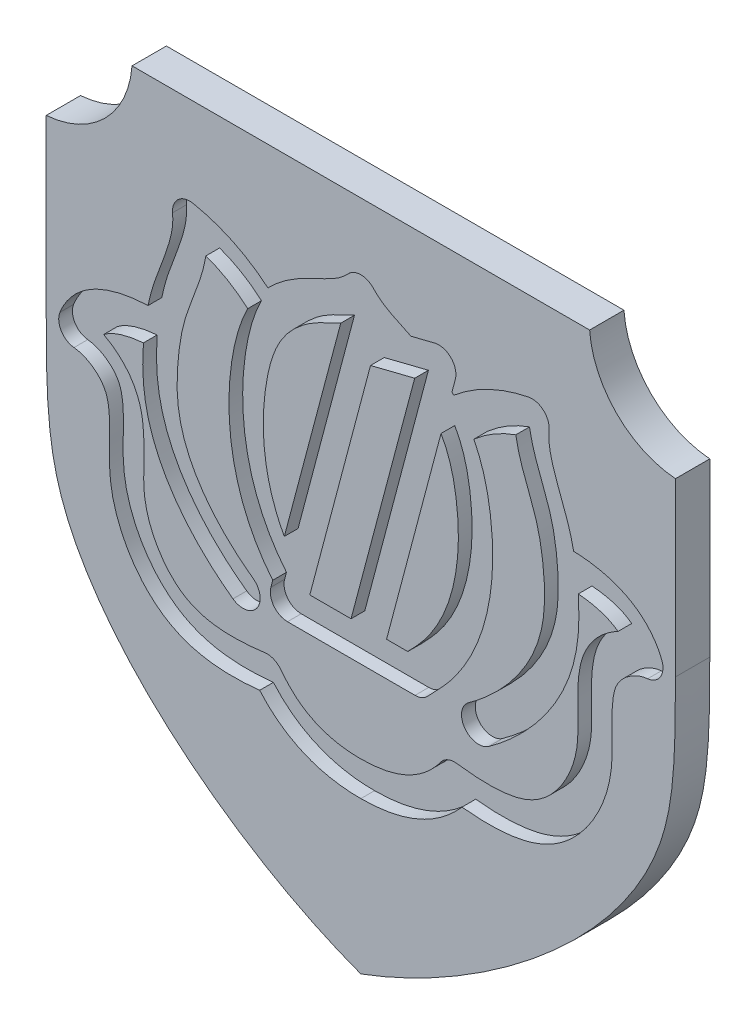
SolidWorks part; units mm, degrees
ref_plane "前视基准面" through (0, 0, 0) normal (0, 0, 1) x (1, 0, 0)
ref_plane "上视基准面" through (0, 0, 0) normal (0, 1, 0) x (1, 0, 0)
ref_plane "右视基准面" through (0, 0, 0) normal (1, 0, 0) x (0, 0, -1)
sketch "草图2" plane through (0, 0, 0) normal (0, 0, 1) x (1, 0, 0)
  line L0 (4.1494, 56.5411) -> (40.8033, 56.5411)
  line L1 (40.8033, 56.5411) -> (40.8033, 44.5411)
  line L2 (22.4764, 6.2707) -> (22.4764, 51.3385) construction
  line L3 (39.8279, 35.4814) -> (22.4764, 35.4814) construction
  line L4 (32.8077, 26.4279) -> (22.4764, 26.4279) construction
  line L5 (40.8033, 44.5411) -> (22.4764, 44.5411) construction
  line L6 (4.1494, 56.5411) -> (4.1494, 44.5411)
  spline S0 degree 3 poles (40.8033, 44.5411) (40.8033, 40.3535) (40.4908, 31.4372) (29.5833, 23.023) (22.4764, 20.3922) knots 0 0 0 0 0.275347 1 1 1 1
  spline S1 degree 3 poles (4.1494, 44.5411) (4.1494, 40.3535) (4.462, 31.4372) (15.3695, 23.023) (22.4764, 20.3922) knots 0 0 0 0 0.275347 1 1 1 1
  point P12 (39.4584, 36.4939)
  point P14 (35.0581, 29.6079)
  point P18 (28.0508, 24.7227)
  point P20 (22.4764, 23.2071)
  point P21 (29.4506, 25.5175)
  point P39 (22.4764, 56.5411)
  dimension "D1" = 32.7641
  dimension "D2" = 18.3269
  dimension "D3" = 17.3516
  dimension "D4" = 10.3313
  dimension "D5" = 6.0357
  dimension "D7" = 9.0535
  dimension "D8" = 9.0597
  dimension "D9" = 12
extrude "凸台-拉伸1" add sketch "草图2" along normal blind 2 contours L1 S0 S1 L6 L0
sketch "草图3" plane through (0, 0, 0) normal (0, 0, -1) x (-1, 0, 0)
  line L0 (39, 165) -> (195, 165) construction
sketch "草图4" plane through (0, 0, 2) normal (0, 0, 1) x (1, 0, 0)
  line L0 (22.4764, 56.5411) -> (22.4764, 20.3922) construction
  line L1 (4.1494, 56.5411) -> (40.8033, 56.5411) construction
  line L2 (18.2036, 37.0255) -> (22.2235, 52.1947) construction
  line L3 (22.2235, 52.1947) -> (27.0152, 53.3994) construction
  line L4 (27.0152, 53.3994) -> (22.676, 37.0255) construction
  line L5 (22.676, 37.0255) -> (18.2036, 37.0255) construction
  line L6 (22.676, 37.0255) -> (25.6338, 37.0255) construction
  line L20 (23.4455, 36.0255) -> (18.2036, 36.0255)
  line L21 (17.2369, 37.2816) -> (17.3448, 37.6886)
  line L23 (27.9818, 53.1433) -> (27.7842, 52.3973)
  line L24 (23.9755, 38.0255) -> (25.2114, 38.0255)
  line L25 (21.9065, 38.0255) -> (19.5031, 38.0255)
  line L26 (19.5031, 38.0255) -> (23.0391, 51.3686)
  line L27 (23.0391, 51.3686) -> (25.6141, 52.016)
  line L28 (25.6141, 52.016) -> (21.9065, 38.0255)
  line L29 (22.676, 36.0255) -> (25.6336, 36.0255)
  line L30 (25.3951, 54.0232) -> (26.7714, 54.3693)
  line L31 (27.1473, 49.9942) -> (23.9755, 38.0255)
  line L32 (18.0197, 40.2355) -> (21.3066, 52.6386)
  line L33 (16.6154, 35.7475) -> (15.6117, 36.4052) construction
  line L34 (16.1946, 37.2177) -> (15.0288, 35.5926) construction
  line L35 (28.7582, 37.2177) -> (29.924, 35.5926) construction
  line L36 (28.7582, 37.2177) -> (29.924, 35.5926) construction
  line L37 (28.3373, 35.7475) -> (29.341, 36.4052) construction
  arc A21 (26.3397, 36.3174) -> (25.6336, 36.0255) centre (25.6336, 37.0255) cw
  arc A22 (18.2036, 36.0255) -> (17.2369, 37.2816) centre (18.2036, 37.0255) cw
  arc A23 (23.2115, 55.3452) -> (21.7426, 55.3475) centre (22.476, 54.6677) ccw
  arc A24 (26.7714, 54.3693) -> (27.9818, 53.1433) centre (27.0152, 53.3994) cw
  arc A25 (32.2425, 54.3779) -> (33.4427, 53.308) centre (32.4468, 53.399) cw
  arc A26 (39.1836, 43.6386) -> (40.002, 45.0103) centre (39.076, 44.6328) ccw
  arc A27 (27.1371, 33.4134) -> (28.064, 33.8057) centre (27.9374, 32.8137) cw
  arc A28 (16.8888, 33.8057) -> (17.8156, 33.4134) centre (17.0154, 32.8137) cw
  arc A29 (12.7102, 54.3779) -> (11.5101, 53.308) centre (12.5059, 53.399) ccw
  arc A30 (4.9508, 45.0103) -> (5.7691, 43.6386) centre (5.8768, 44.6328) ccw
  arc A33 (16.1946, 37.2177) -> (15.0288, 35.5926) centre (15.6117, 36.4052) cw
  arc A34 (28.7582, 37.2177) -> (29.924, 35.5926) centre (29.3411, 36.4052) ccw
  spline S0 degree 3 poles (22.4764, 54.6675) (21.5957, 53.6967) (19.4078, 53.1306) (16.7241, 50.7619) (15.5245, 46.4292) (15.8922, 41.6848) (17.6479, 38.8117) (18.4474, 37.9456) knots 0 0 0 0 0.184464 0.328772 0.505894 0.829967 1 1 1 1 construction
  spline S1 degree 3 poles (22.4764, 54.6675) (23.2535, 53.8109) (24.3007, 53.4628) (25.2837, 52.9641) knots 0 0 0 0 0.16277 0.16277 0.16277 0.16277 construction
  spline S2 degree 2 poles (26.5054, 37.9456) (25.9014, 37.2913) (25.6338, 37.0255) knots 0 0 0 1 1 1 construction
  spline S3 degree 3 poles (26.6622, 52.0676) (27.1111, 51.6935) (28.3381, 50.3666) (29.4283, 46.4292) (29.0605, 41.6848) (27.3048, 38.8117) (26.5054, 37.9456) knots 0.243353 0.243353 0.243353 0.243353 0.328772 0.505894 0.829967 1 1 1 1 construction
  spline S4 degree 2 poles (17.157, 50.8362) (15.2274, 52.8532) (12.506, 53.3994) knots 0 0 0 1 1 1 construction
  spline S5 degree 3 poles (12.506, 53.3994) (12.6565, 51.9187) (11.4669, 49.5818) (10.8419, 46.8735) (10.457, 40.4605) (14.5182, 36.9921) (16.6154, 35.7475) knots 0 0 0 0 0.222641 0.34958 0.494422 1 1 1 1 construction
  spline S6 degree 3 poles (10.9236, 46.9057) (9.0932, 47) (6.6678, 46.6159) (5.8768, 44.6327) knots 0 0 0 0 1 1 1 1 construction
  spline S7 degree 3 poles (5.8768, 44.6327) (6.9592, 44.5209) (8.5039, 43.4661) (8.9816, 40.7155) (8.4519, 37.2808) (11.3933, 32.42) (15.3797, 32.6) (17.0154, 32.8139) knots 0 0 0 0 0.17617 0.249065 0.433904 0.728589 1 1 1 1 construction
  spline S8 degree 2 poles (17.0154, 32.8139) (18.934, 30.239) (22.4764, 30.239) knots 0 0 0 1 1 1 construction
  spline S9 degree 2 poles (27.9374, 32.8139) (26.0188, 30.239) (22.4764, 30.239) knots 0 0 0 1 1 1 construction
  spline S10 degree 3 poles (39.076, 44.6327) (37.9935, 44.5209) (36.4489, 43.4661) (35.9712, 40.7155) (36.5009, 37.2808) (33.5594, 32.42) (29.5731, 32.6) (27.9374, 32.8139) knots 0 0 0 0 0.17617 0.249065 0.433904 0.728589 1 1 1 1 construction
  spline S11 degree 3 poles (34.0292, 46.9057) (35.8596, 47) (38.285, 46.6159) (39.076, 44.6327) knots 0 0 0 0 1 1 1 1 construction
  spline S12 degree 3 poles (32.4468, 53.3994) (32.2963, 51.9187) (33.4859, 49.5818) (34.1109, 46.8735) (34.4958, 40.4605) (30.4346, 36.9921) (28.3373, 35.7475) knots 0 0 0 0 0.222641 0.34958 0.494422 1 1 1 1 construction
  spline S13 degree 2 poles (27.7958, 50.8362) (29.7253, 52.8532) (32.4468, 53.3994) knots 0 0 0 1 1 1 construction
  spline S14 degree 3 poles (9.8113, 45.8961) (9.5472, 45.8759) (8.9669, 45.8016) (8.146, 45.561) (7.704, 45.3196) (7.4963, 45.162) knots 0.206327 0.206327 0.206327 0.206327 0.358363 0.537545 0.716726 0.716726 0.716726 0.716726
  spline S15 degree 3 poles (21.3066, 52.6386) (21.2982, 52.6345) (20.9026, 52.4399) (20.1528, 52.1116) (19.2561, 51.5915) (18.4482, 50.895) (17.8305, 50.1052) (17.2406, 48.8823) (16.8387, 47.0036) (16.7375, 44.6753) (17.0676, 42.4325) (17.6065, 40.9968) (17.9869, 40.2945) (18.0197, 40.2355) knots 0.097335 0.097335 0.097335 0.097335 0.098633 0.158724 0.218815 0.278906 0.338997 0.399088 0.519271 0.639453 0.759635 0.879818 0.890912 0.890912 0.890912 0.890912
  spline S16 degree 2 poles (17.0649, 52.2933) (16.4131, 52.8417) (15.085, 53.611) (14.0068, 54.0395) (13.219, 54.2696) (12.7888, 54.3616) (12.7102, 54.3779) knots 0.183706 0.183706 0.183706 0.466542 0.699814 0.855328 0.971963 0.999219 0.999219 0.999219
  spline S17 degree 3 poles (11.5101, 53.308) (11.5186, 53.2145) (11.5283, 53.0696) (11.5208, 52.7247) (11.4383, 52.1045) (11.1453, 51.1255) (10.648, 49.8889) (10.2828, 48.8082) (10.1286, 48.1504) (10.0805, 47.9132) knots -0.000426 -0.000426 -0.000426 -0.000426 0.015831 0.032512 0.065874 0.132597 0.19932 0.266044 0.302183 0.302183 0.302183 0.302183
  spline S18 degree 2 poles (27.8873, 52.2928) (28.5393, 52.8415) (29.8678, 53.611) (30.946, 54.0395) (31.7338, 54.2696) (32.164, 54.3616) (32.2425, 54.3779) knots 0.183578 0.183578 0.183578 0.466542 0.699814 0.855328 0.971963 0.999219 0.999219 0.999219
  spline S19 degree 3 poles (35.1415, 45.8961) (35.1439, 45.8624) (35.1826, 45.2963) (35.2067, 44.125) (34.9587, 42.4085) (34.2455, 40.3437) (33.1184, 38.5891) (31.8089, 37.1551) (30.8339, 36.277) (30.2083, 35.7966) (29.924, 35.5926) knots 0.395261 0.395261 0.395261 0.395261 0.39949 0.466213 0.532937 0.59966 0.733107 0.79983 0.866553 0.92413 0.92413 0.92413 0.92413
  spline S20 degree 3 poles (9.8113, 45.8961) (9.8089, 45.8624) (9.7701, 45.2963) (9.746, 44.125) (9.9941, 42.4085) (10.7073, 40.3437) (11.8343, 38.5891) (13.1439, 37.1551) (14.1188, 36.277) (14.7445, 35.7966) (15.0288, 35.5926) knots 0.395261 0.395261 0.395261 0.395261 0.39949 0.466213 0.532937 0.59966 0.733107 0.79983 0.866553 0.92413 0.92413 0.92413 0.92413
  spline S21 degree 3 poles (15.891, 50.6646) (15.4915, 49.8916) (14.959, 48.0881) (14.7027, 45.3428) (14.9796, 42.4266) (15.7623, 40.118) (16.6554, 38.5818) (17.1451, 37.9305) (17.3448, 37.6886) knots 0.362153 0.362153 0.362153 0.362153 0.474145 0.605609 0.737073 0.868536 0.934268 0.975477 0.975477 0.975477 0.975477
  spline S22 degree 3 poles (29.061, 50.664) (29.3118, 50.1765) (29.7617, 48.9767) (30.0989, 47.0765) (30.2424, 44.2832) (29.7702, 41.4989) (28.5892, 38.9584) (27.7244, 37.7919) (27.2402, 37.2673) knots 0.362177 0.362177 0.362177 0.362177 0.432515 0.527095 0.621676 0.810838 0.905419 1 1 1 1
  spline S24 degree 3 poles (10.0805, 47.9132) (10.0617, 47.9126) (9.719, 47.9) (9.0198, 47.8405) (7.9924, 47.6233) (6.9822, 47.2341) (6.0441, 46.6265) (5.3858, 45.8778) (5.076, 45.3109) (4.9683, 45.0532) (4.9508, 45.0103) knots 0.14203 0.14203 0.14203 0.14203 0.150826 0.301651 0.452477 0.603303 0.754129 0.904954 0.980367 0.99907 0.99907 0.99907 0.99907
  spline S25 degree 3 poles (5.7691, 43.6386) (5.7786, 43.6375) (5.829, 43.6319) (5.9212, 43.6185) (6.1675, 43.5652) (6.6428, 43.3843) (7.1523, 43.0168) (7.5016, 42.5627) (7.7212, 42.1114) (7.8531, 41.2853) (7.8472, 40.1402) (7.8041, 38.8806) (7.923, 37.4519) (8.3502, 36.0352) (9.027, 34.7129) (9.9441, 33.5402) (11.0941, 32.5823) (12.4678, 31.962) (13.8719, 31.6914) (15.2749, 31.6454) (16.1434, 31.7094) (16.5837, 31.7558) knots 0.000073 0.000073 0.000073 0.000073 0.001868 0.01001 0.026295 0.058865 0.124004 0.156574 0.189143 0.254282 0.319422 0.384561 0.4497 0.514839 0.579978 0.645118 0.710257 0.775396 0.840535 0.905674 0.970814 0.970814 0.970814 0.970814
  spline S26 degree 2 poles (16.5837, 31.7558) (17.3985, 30.8142) (19.154, 29.82) (21.1288, 29.2354) (22.4764, 29.239) knots 0.081569 0.081569 0.081569 0.425981 0.655589 1 1 1
  spline S27 degree 2 poles (22.4764, 29.239) (23.824, 29.2354) (25.7988, 29.82) (27.5542, 30.8142) (28.369, 31.7558) knots 0.081569 0.081569 0.081569 0.425981 0.655589 1 1 1
  spline S28 degree 3 poles (28.369, 31.7558) (28.8094, 31.7094) (29.6779, 31.6454) (31.0809, 31.6914) (32.485, 31.962) (33.8587, 32.5823) (35.0086, 33.5402) (35.9258, 34.7129) (36.6025, 36.0352) (37.0297, 37.4519) (37.1487, 38.8806) (37.1056, 40.1402) (37.0996, 41.2853) (37.2315, 42.1114) (37.4512, 42.5627) (37.8005, 43.0168) (38.31, 43.3843) (38.7853, 43.5652) (39.0316, 43.6185) (39.1238, 43.6319) (39.1741, 43.6375) (39.1836, 43.6386) knots -0.071414 -0.071414 -0.071414 -0.071414 -0.006275 0.058865 0.124004 0.189143 0.254282 0.319422 0.384561 0.4497 0.514839 0.579978 0.645118 0.710257 0.742826 0.775396 0.840535 0.873105 0.88939 0.897532 0.899327 0.899327 0.899327 0.899327
  spline S29 degree 3 poles (40.002, 45.0103) (39.9845, 45.0532) (39.8768, 45.3109) (39.567, 45.8778) (38.9087, 46.6265) (37.9706, 47.2341) (36.9604, 47.6233) (35.933, 47.8405) (35.2338, 47.9) (34.8911, 47.9126) (34.8722, 47.9132) knots 0.207536 0.207536 0.207536 0.207536 0.226239 0.301651 0.452477 0.603303 0.754129 0.904954 1.05578 1.064576 1.064576 1.064576 1.064576
  spline S32 degree 3 poles (25.3951, 54.0232) (25.3358, 54.0515) (25.1051, 54.1605) (24.5656, 54.4091) (23.995, 54.702) (23.5925, 54.9868) (23.3784, 55.1728) (23.285, 55.2658) (23.2202, 55.3357) (23.2115, 55.3452) knots -0.034078 -0.034078 -0.034078 -0.034078 -0.0249 0.00191 0.05553 0.08234 0.095745 0.10915 0.111193 0.111193 0.111193 0.111193
  spline S33 degree 3 poles (21.7426, 55.3475) (21.6849, 55.2852) (21.5224, 55.1163) (21.1928, 54.8577) (20.5595, 54.4806) (19.5846, 54.0559) (18.2255, 53.3372) (17.4285, 52.671) (17.066, 52.2944) (17.0649, 52.2933) knots -0.000191 -0.000191 -0.000191 -0.000191 0.014022 0.046888 0.079754 0.145486 0.211218 0.27695 0.277144 0.277144 0.277144 0.277144
  spline S36 degree 3 poles (27.1473, 49.9942) (27.3948, 49.5743) (27.7896, 48.5994) (28.1081, 46.8451) (28.2304, 44.4136) (27.8237, 42.059) (26.8549, 39.9824) (26.1609, 39.0467) (25.7706, 38.6239) knots 0.345263 0.345263 0.345263 0.345263 0.432515 0.527095 0.621676 0.810838 0.905419 1 1 1 1
  spline S37 degree 2 poles (25.7706, 38.6239) (25.4366, 38.2621) (25.2114, 38.0255) knots 0 0 0 0.558171 0.558171 0.558171
  spline S40 degree 2 poles (29.061, 50.664) (30.1611, 51.6257) (31.5023, 52.1036) knots 0.152942 0.152942 0.152942 0.755869 0.755869 0.755869
  spline S41 degree 3 poles (31.5023, 52.1036) (31.5734, 51.6597) (31.814, 50.7663) (32.2635, 49.5977) (32.6474, 48.5863) (32.8913, 47.6863) (33.0662, 46.6691) (33.1859, 45.435) (33.1872, 44.1513) (32.96, 42.5897) (32.2331, 40.8253) (30.8818, 39.0126) (29.6367, 37.8739) (28.9385, 37.3471) (28.7581, 37.2177) knots 0.057104 0.057104 0.057104 0.057104 0.116035 0.174966 0.233897 0.292828 0.351759 0.41069 0.469621 0.528552 0.646414 0.764276 0.882138 0.924123 0.924123 0.924123 0.924123
  spline S44 degree 2 poles (15.891, 50.6646) (14.7912, 51.6259) (13.4504, 52.1036) knots 0.153139 0.153139 0.153139 0.755869 0.755869 0.755869
  spline S45 degree 3 poles (13.4504, 52.1036) (13.3794, 51.6597) (13.1387, 50.7663) (12.6893, 49.5977) (12.3054, 48.5863) (12.0615, 47.6863) (11.8866, 46.6691) (11.7669, 45.435) (11.7656, 44.1513) (11.9927, 42.5897) (12.7197, 40.8253) (14.0709, 39.0126) (15.316, 37.8739) (16.0141, 37.3472) (16.1946, 37.2177) knots 0.057104 0.057104 0.057104 0.057104 0.116035 0.174966 0.233897 0.292828 0.351759 0.41069 0.469621 0.528552 0.646414 0.764276 0.882138 0.924114 0.924114 0.924114 0.924114
  spline S53 degree 3 poles (7.4963, 45.162) (7.9387, 44.9307) (8.5478, 44.4732) (9.1793, 43.6762) (9.6543, 42.7284) (9.8421, 41.5525) (9.8556, 39.9074) (9.7787, 38.5047) (10.0624, 37.2303) (10.5883, 35.9455) (11.6456, 34.5664) (13.2085, 33.7527) (14.9546, 33.6263) (16.1961, 33.7205) (16.7221, 33.7844) (16.8888, 33.8057) knots 0.064208 0.064208 0.064208 0.064208 0.124704 0.154952 0.1852 0.245697 0.306193 0.427186 0.487682 0.548178 0.669171 0.790164 0.911157 0.971653 0.999696 0.999696 0.999696 0.999696
  spline S54 degree 2 poles (17.8156, 33.4134) (17.8661, 33.3461) (18.053, 33.1079) (18.5721, 32.5443) (19.5345, 31.8512) (21.1802, 31.2449) (22.4764, 31.239) knots 0.000309 0.000309 0.000309 0.028078 0.113334 0.317949 0.59077 1 1 1
  spline S55 degree 2 poles (22.4764, 31.239) (23.7725, 31.2449) (25.4182, 31.8512) (26.3807, 32.5443) (26.8997, 33.1079) (27.0867, 33.3461) (27.1371, 33.4134) knots -0.091281 -0.091281 -0.091281 0.317949 0.59077 0.795385 0.880641 0.90841 0.90841 0.90841
  spline S56 degree 3 poles (28.064, 33.8057) (28.2306, 33.7844) (28.7566, 33.7205) (29.9981, 33.6263) (31.7443, 33.7527) (33.3071, 34.5664) (34.3645, 35.9455) (34.8903, 37.2303) (35.1741, 38.5047) (35.0971, 39.9074) (35.1106, 41.5525) (35.2985, 42.7284) (35.7735, 43.6762) (36.405, 44.4732) (37.0141, 44.9307) (37.4565, 45.162) knots 0.096661 0.096661 0.096661 0.096661 0.124704 0.1852 0.306193 0.427186 0.548178 0.608675 0.669171 0.790164 0.85066 0.911157 0.941405 0.971653 1.032149 1.032149 1.032149 1.032149
  spline S57 degree 3 poles (37.4565, 45.162) (37.2488, 45.3196) (36.8067, 45.561) (35.9859, 45.8016) (35.4056, 45.8759) (35.1415, 45.8961) knots 0 0 0 0 0.179182 0.358363 0.510399 0.510399 0.510399 0.510399
  spline S64 degree 3 poles (27.7842, 52.3973) (27.8189, 52.3629) (27.8532, 52.328) (27.8873, 52.2928) knots 0.270817 0.270817 0.270817 0.270817 0.276986 0.276986 0.276986 0.276986
  spline S65 degree 2 poles (27.2402, 37.2673) (26.8875, 36.8852) (26.4768, 36.4542) (26.3516, 36.3293) (26.3397, 36.3174) knots 0 0 0 0.579983 0.966639 1.007902 1.007902 1.007902
  spline S68 degree 2 poles (27.0732, 51.5274) (27.114, 51.5702) (27.1552, 51.6124) knots 0 0 0 0.019171 0.019171 0.019171
  spline S69 degree 3 poles (33.4427, 53.308) (33.4341, 53.2145) (33.4244, 53.0696) (33.432, 52.7247) (33.5144, 52.1045) (33.8074, 51.1255) (34.3047, 49.8889) (34.6699, 48.8082) (34.8241, 48.1504) (34.8722, 47.9132) knots -0.000426 -0.000426 -0.000426 -0.000426 0.015831 0.032512 0.065874 0.132597 0.19932 0.266044 0.302183 0.302183 0.302183 0.302183
  point P135 (0, 0)
  dimension "D2" = 1.2
  dimension "D1" = 1
extrude "切除-拉伸1" cut sketch "草图4" against normal blind 0.8
sketch "草图13" plane through (0, 56.5411, 0) normal (0, 1, 0) x (1, 0, 0)
  line L0 (4.1494, 0) -> (40.8033, 0)
  line L1 (40.8033, 0) -> (40.8033, -2)
  line L2 (40.8033, -2) -> (4.1494, -2)
  line L3 (4.1494, -2) -> (4.1494, 0)
extrude "凸台-拉伸2" add sketch "草图13" along normal blind 3
sketch "草图14" plane through (0, 0, 2) normal (0, 0, 1) x (1, 0, 0)
  line L0 (4.1494, 59.5411) -> (4.1494, 44.5411) construction
  line L1 (4.1494, 59.5411) -> (40.8033, 59.5411) construction
  line L2 (22.4764, 59.5411) -> (22.4764, 20.3922) construction
  line L3 (3.7429, 59.9476) -> (4.1494, 59.5411) construction
  line L4 (9.1494, 59.5411) -> (4.1494, 59.5411)
  line L5 (4.1494, 59.5411) -> (4.1494, 54.5411)
  line L6 (40.8033, 59.5411) -> (40.8033, 54.5411)
  line L7 (35.8033, 59.5411) -> (40.8033, 59.5411)
  arc A0 (4.1494, 54.5411) -> (9.1494, 59.5411) centre (3.7429, 59.9476) ccw
  arc A1 (40.8033, 54.5411) -> (35.8033, 59.5411) centre (41.2099, 59.9476) cw
  dimension "D1" = 135
  dimension "D2" = 5
extrude "切除-拉伸7" cut sketch "草图14" against normal through all
